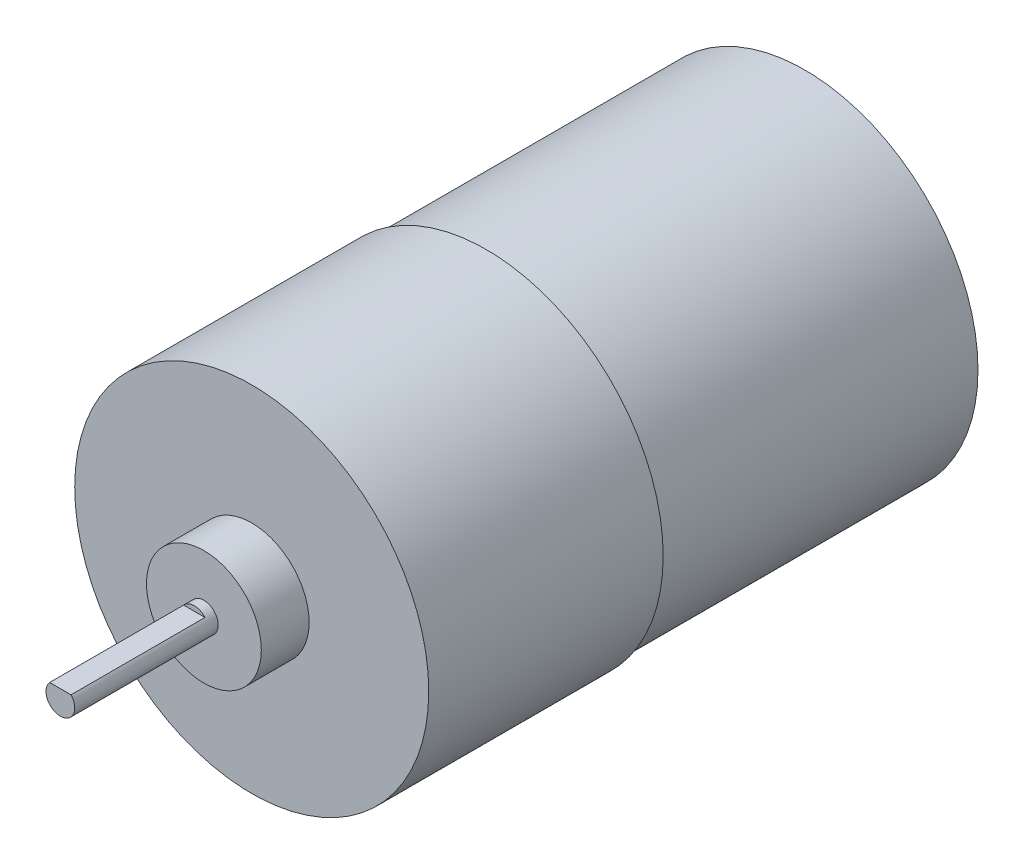
SolidWorks part; units mm, degrees
ref_plane "Front Plane" through (0, 0, 0) normal (0, 0, 1) x (1, 0, 0)
ref_plane "Top Plane" through (0, 0, 0) normal (0, 1, 0) x (1, 0, 0)
ref_plane "Right Plane" through (0, 0, 0) normal (1, 0, 0) x (0, 0, -1)
sketch "Sketch1" plane through (0, 0, 0) normal (0, 0, 1) x (1, 0, 0)
  circle A0 centre (0, 0) radius 18.1
  dimension "D1" = 36.2
extrude "Boss-Extrude1" add sketch "Sketch1" along normal blind 33.3
sketch "Sketch2" plane through (0, 0, 33.3) normal (0, 0, 1) x (1, 0, 0)
  circle A0 centre (0, 0) radius 18.5
  dimension "D1" = 37
extrude "Boss-Extrude2" add sketch "Sketch2" along normal blind 24.5
sketch "Sketch3" plane through (0, 0, 57.8) normal (0, 0, 1) x (1, 0, 0)
  circle A0 centre (0, 0) radius 6
  dimension "D1" = 12
extrude "Boss-Extrude3" add sketch "Sketch3" along normal blind 5
sketch "Sketch4" plane through (0, 0, 62.8) normal (0, 0, 1) x (1, 0, 0)
  circle A0 centre (0, 0) radius 1.5
  dimension "D1" = 3
extrude "Boss-Extrude4" add sketch "Sketch4" along normal blind 15
sketch "Sketch8" plane through (0, 0, 77.8) normal (0, 0, 1) x (1, 0, 0)
  line L0 (-1.118, 1) -> (1.118, 1)
  arc A1 (1.118, 1) -> (-1.118, 1) centre (0, 0) ccw
  dimension "D1" = 3
  dimension "D2" = 1
extrude "Cut-Extrude2" cut sketch "Sketch8" against normal blind 14
equation "\"Material Thickness\" = .25in"
equation "\"Motor Mount Tab Thickness\" = 100mm"
equation "\"Motor Mount Tab Height\" = 40mm"
equation "\"D1@Sketch1\"=\"Motor Rear Diameter\""
equation "\"D1@Sketch3\"=\"Motor Front Diameter\""
equation "\"Motor Shaft Diameter\" = 3mm"
equation "\"D1@Sketch4\"=\"Motor Shaft Diameter\""
equation "\"Wheel Thickness\"= 1in"
equation "\"Wheel Diameter\"= 3in"
equation "\"Motor Rear Diameter\" = 36.2mm"
equation "\"Motor Front Diameter\" = 12mm"
equation "\"Wheel Cutout Diameter\"= 2cm"
equation "\"D1@Sketch8\"=\"Motor Shaft Diameter\""
equation "\"D2@Sketch8\"=(\"Motor Shaft Diameter\"/2)-.5mm"
